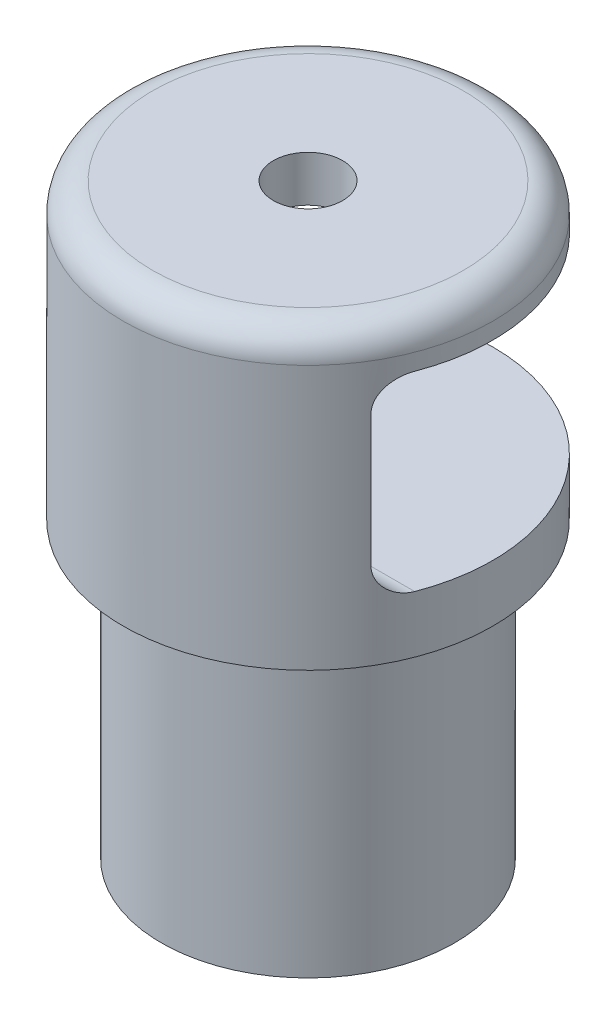
SolidWorks part; units mm, degrees
ref_plane "Front Plane" through (0, 0, 0) normal (0, 0, 1) x (1, 0, 0)
ref_plane "Top Plane" through (0, 0, 0) normal (0, 1, 0) x (1, 0, 0)
ref_plane "Right Plane" through (0, 0, 0) normal (1, 0, 0) x (0, 0, -1)
sketch "Sketch1" plane through (0, 0, 0) normal (0, 1, 0) x (1, 0, 0)
  circle A0 centre (0, 0) radius 8.001
  dimension "D1" = 16.002
extrude "Boss-Extrude1" add sketch "Sketch1" along normal blind 25.4
sketch "Sketch2" plane through (0, 0, 0) normal (0, -1, 0) x (-1, 0, 0)
  circle A0 centre (0, 0) radius 4.699
  circle A1 centre (0, 0) radius 6.35
  circle A2 centre (0, 0) radius 8.001
  circle M1 centre (0, 0) radius 8.001
  dimension "D1" = 9.398
  dimension "D2" = 12.7
extrude "Cut-Extrude1" cut sketch "Sketch2" against normal blind 12.7 contours A0 | A1 M1
sketch "Sketch3" plane through (0, 0, 0) normal (0, 0, 1) x (1, 0, 0)
  line L0 (8.001, 25.4) -> (-8.001, 25.4) construction
  line L1 (-4.1275, 25.4) -> (4.1275, 25.4)
  line L2 (-4.1275, 25.4) -> (-4.1275, 15.24)
  line L3 (-4.1275, 15.24) -> (4.1275, 15.24)
  line L4 (4.1275, 25.4) -> (4.1275, 15.24)
  line L5 (-8.001, 25.4) -> (-8.001, 12.7) construction
  line L6 (-8.001, 15.24) -> (-6.6675, 15.24)
  line L7 (-8.001, 15.24) -> (-8.001, 25.4)
  line L8 (-8.001, 25.4) -> (-6.6675, 25.4)
  line L9 (-6.6675, 15.24) -> (-6.6675, 25.4)
  line L11 (6.6675, 15.24) -> (8.001, 15.24)
  line L12 (6.6675, 15.24) -> (6.6675, 25.4)
  line L13 (6.6675, 25.4) -> (8.001, 25.4)
  line L14 (8.001, 15.24) -> (8.001, 25.4)
  dimension "D1" = 15.24
  dimension "D2" = 0
  dimension "D3" = 8.255
  dimension "D4" = 4.1275
  dimension "D5" = 2.54
  dimension "D6" = 2.54
extrude "Cut-Extrude2" [suppressed] cut sketch "Sketch3" against normal through all and the other way through all
sketch "Sketch4" [suppressed] plane through (6.6675, 0, 0) normal (1, 0, 0) x (0, 0, -1)
  line L0 (0, 25.4) -> (0, 15.24) construction
  line L1 (4.4227, 25.4) -> (-4.4227, 25.4) construction
  line L2 (4.4227, 15.24) -> (-4.4227, 15.24) construction
  line L3 (-4.8594, 21.8008) -> (-6.8587, 15.24)
  line L4 (-6.8587, 15.24) -> (-6.8587, 50.8)
  line L5 (7.0182, 15.24) -> (4.8258, 21.907)
  line L6 (-6.8587, 50.8) -> (6.956, 50.8)
  line L7 (6.956, 50.8) -> (7.0182, 15.24)
  arc A0 (4.8258, 21.907) -> (-4.8594, 21.8008) centre (0, 20.32) ccw
  circle A1 centre (0, 20.32) radius 1.5875
  line M2 (4.4227, 25.4) -> (-4.4227, 25.4)
  line M3 (-4.4227, 25.4) -> (-4.4227, 15.24)
  line M5 (4.4227, 15.24) -> (4.4227, 25.4)
  dimension "D1" = 3.175
  dimension "D2" = 25.4
extrude "Cut-Extrude3" [suppressed] cut sketch "Sketch4" against normal through all contours A0 L5 L7 L6 L4 L3 M3 M2 M5 | A1 L0 | L0 A1 | A0 M2 M3 | A0 M5 M2
fillet "Fillet1" [suppressed] radius 2.54
sketch "Sketch5" plane through (0, 0, 0) normal (0, 0, 1) x (1, 0, 0)
  line L0 (-8.001, 12.7) -> (-8.001, 25.8799) construction
  line L1 (-10.1647, 15.1624) -> (11.0495, 15.1624)
  line L2 (-10.1647, 15.1624) -> (-10.1647, 23.4174)
  line L3 (-10.1647, 23.4174) -> (11.0495, 23.4174)
  line L4 (11.0495, 15.1624) -> (11.0495, 23.4174)
  line L5 (-8.001, 19.2899) -> (8.001, 19.2899) construction
  line L6 (8.001, 12.7) -> (8.001, 25.4) construction
  dimension "D1" = 8.255
  dimension "D2" = 4.1275
extrude "Cut-Extrude4" cut sketch "Sketch5" against normal blind 12.7 and the other way blind 4.1275
sketch "Sketch6" plane through (0, 25.4, 0) normal (0, 1, 0) x (1, 0, 0)
  circle A0 centre (0, 0) radius 1.5
  dimension "D1" = 3
extrude "Cut-Extrude5" cut sketch "Sketch6" against normal up to next
fillet "Fillet2" radius 1.27 2 edges at (0, 23.4174, 4.1275) (0, 15.1624, 4.1275)
fillet "Fillet3" radius 1.27 1 edges at (0, 25.4, 8.001)
sketch "Sketch7" plane through (0, 15.1624, 0) normal (0, 1, 0) x (1, 0, 0)
  circle A0 centre (0, 0) radius 1.25
  dimension "D1" = 2.5
extrude "Cut-Extrude6" cut sketch "Sketch7" against normal up to next
equation "\"LinkID\"= .5in"
equation "\"LinkTHNK\"= .065in"
equation "\"TieRodWidth\"= .325in"
equation "\"D1@Sketch1\"=\"LinkID\"+2*(\"LinkTHNK\")"
equation "\"D1@Sketch2\"=\"LinkID\"-2*(\"LinkTHNK\")"
equation "\"D2@Sketch2\"=\"LinkID\""
equation "\"D3@Sketch3\"=\"TieRodWidth\""
equation "\"D4@Sketch3\"=\"D3@Sketch3\"/2"
equation "\"D6@Sketch3\"=\"D5@Sketch3\""
equation "\"D1@Sketch5\"=\"TieRodWidth\""
equation "\"D2@Sketch5\"=\"D1@Sketch5\"/2"
equation "\"D2@Cut-Extrude4\"=\"TieRodWidth\"/2"
